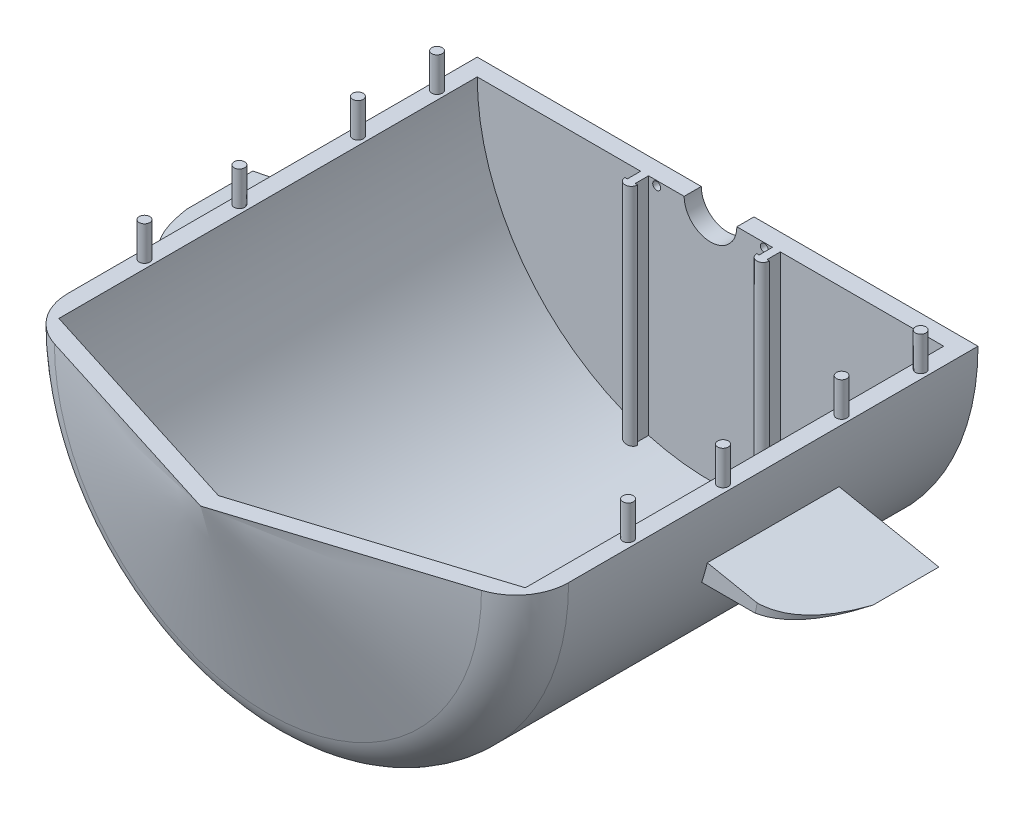
SolidWorks part; units mm, degrees
material "PVC 0.007 Plasticized"
ref_plane "Front Plane" through (0, 0, 0) normal (0, 0, 1) x (1, 0, 0)
ref_plane "Top Plane" through (0, 0, 0) normal (0, 1, 0) x (1, 0, 0)
ref_plane "Right Plane" through (0, 0, 0) normal (1, 0, 0) x (0, 0, -1)
sketch "Sketch1" plane through (0, 0, 0) normal (0, 1, 0) x (1, 0, 0)
  line L0 (0, 75) -> (95, 75)
  line L1 (95, 75) -> (95, -95)
  line L2 (95, -95) -> (0, -125)
  line L3 (0, -125) -> (0, 75) construction
  line L4 (0, 75) -> (0, -125)
  dimension "D1" = 200
  dimension "D2" = 170
  dimension "D3" = 95
  dimension "D4" = 75
  dimension "D5" = 95
revolve "Revolve1" add sketch "Sketch1" angle 180 about L3
sketch "Sketch2" plane through (0, 0, 0) normal (0, 1, 0) x (1, 0, 0)
  line L5 (0, 68.5) -> (0, -118.1836) construction
  line L6 (0, 68.5) -> (0, -118.1836)
  line L10 (-88.5, -90.2362) -> (0, -118.1836)
  line L11 (0, -118.1836) -> (88.5, -90.2362)
  line L12 (88.5, -90.2362) -> (88.5, 68.5)
  line L13 (88.5, 68.5) -> (-88.5, 68.5)
  line L14 (-88.5, 68.5) -> (-88.5, -90.2362)
  line L16 (0, -118.1836) -> (88.5, -90.2362)
  line L17 (88.5, -90.2362) -> (88.5, 68.5)
  line L18 (88.5, 68.5) -> (0, 68.5)
  dimension "D1" = 6.5
revolve "Cut-Revolve3" cut sketch "Sketch2" angle 360 about L5
sketch "Sketch3" plane through (0, 0, 0) normal (0, 1, 0) x (1, 0, 0)
  line L0 (-88.5, 68.5) -> (-95, 68.5) construction
  line L1 (-95, -95) -> (-95, 75) construction
  line L2 (-91.75, 68.5) -> (-91.75, -96.0263) construction
  line L3 (0, -125) -> (-95, -95) construction
  line L4 (0, 68.5) -> (0, -90.2362) construction
  line L5 (-88.5, 68.5) -> (88.5, 68.5) construction
  line L6 (88.5, -90.2362) -> (-88.5, -90.2362) construction
  circle A1 centre (-91.75, 56.5) radius 2
  circle A2 centre (-91.75, 26.5) radius 2
  circle A3 centre (-91.75, -18.5) radius 2
  circle A4 centre (-91.75, -54.5) radius 2
  circle A5 centre (91.75, -54.5) radius 2
  circle A6 centre (91.75, -18.5) radius 2
  circle A7 centre (91.75, 26.5) radius 2
  circle A8 centre (91.75, 56.5) radius 2
  dimension "D1" = 4
  dimension "D2" = 30
  dimension "D3" = 45
  dimension "D4" = 36
  dimension "D5" = 12
extrude "Boss-Extrude1" add sketch "Sketch3" along normal blind 13
sketch "Sketch4" plane through (0, 0, 0) normal (0, 0, 1) x (1, 0, 0)
  line L1 (88.5, 0) -> (-88.5, 0)
  line L2 (88.5, 0) -> (-88.5, 0)
  line L6 (0, -88.5) -> (0, -52) construction
  line L7 (-76.787, -44) -> (76.787, -44)
  line L8 (-71.6118, -52) -> (71.6118, -52)
  arc A1 (-88.5, 0) -> (88.5, 0) centre (0, 0) ccw
  arc A2 (-88.5, 0) -> (88.5, 0) centre (0, 0) ccw
  dimension "D1" = 0
  dimension "D2" = 44.5
  dimension "D3" = 8
sketch "Sketch5" plane through (0, 0, 0) normal (0, 1, 0) x (1, 0, 0)
  line L1 (23.5, 63.4476) -> (23.5, 68.5)
  line L4 (0, 0) -> (0, 89.957) construction
  line L8 (-27.4, 63.4476) -> (-26.5, 63.4476)
  line L9 (-26.5, 63.4476) -> (-26.5, 68.5)
  line L10 (-22.6, 63.4476) -> (-23.5, 63.4476)
  line L11 (-23.5, 63.4476) -> (-23.5, 68.5)
  line L12 (88.5, 68.5) -> (-88.5, 68.5) construction
  line L13 (-23.5, 68.5) -> (-26.5, 68.5)
  line L14 (22.6, 63.4476) -> (23.5, 63.4476)
  line L15 (27.4, 63.4476) -> (26.5, 63.4476)
  line L16 (26.5, 63.4476) -> (26.5, 68.5)
  line L17 (23.5, 68.5) -> (26.5, 68.5)
  arc A0 (-27.4, 63.4476) -> (-22.6, 63.4476) centre (-25, 63.4476) ccw
  arc A2 (27.4, 63.4476) -> (22.6, 63.4476) centre (25, 63.4476) cw
  dimension "D2" = 2.4
  dimension "D5" = 3
  dimension "D1" = 5.0524
  dimension "D3" = 25
extrude "Boss-Extrude8" add sketch "Sketch5" against normal up to surface (85.5657 mm away)
extrude "Boss-Extrude10" [suppressed] add sketch "Sketch4" along normal mid plane 120 contours L7 A2 L8
sketch "Sketch7" plane through (0, 0, -68.5) normal (0, 0, 1) x (1, 0, 0)
  line L0 (0, 0) -> (20.4252, -1.75) construction
  line L2 (0, 21.148) -> (0, -18.5427) construction
  line L3 (0, 0) -> (95, 0) construction
  circle A0 centre (0, 0) radius 10
  circle A1 centre (20.4252, -1.75) radius 1.5
  circle A2 centre (-20.4252, -1.75) radius 1.5
  dimension "D1" = 20
  dimension "D2" = 3
  dimension "D4" = 1.75
  dimension "D3" = 20.5
extrude "Cut-Extrude1" cut sketch "Sketch7" against normal blind 10
sketch "Sketch8" plane through (0, 0, 0) normal (0, 0, 1) x (1, 0, 0)
  line L0 (0, 0) -> (0, -30) construction
  line L1 (0, -30) -> (90.1388, -30) construction
  line L2 (90.1388, -30) -> (-90.1388, -30) construction
  line L3 (90.1388, -30) -> (130.1388, -30)
  line L4 (130.1388, -30) -> (92.2971, -22.5)
  line L5 (92.2971, -22.5) -> (90.1388, -30)
  line L6 (-130.1388, -30) -> (-92.2971, -22.5)
  line L7 (-90.1388, -30) -> (-130.1388, -30)
  line L8 (-92.2971, -22.5) -> (-90.1388, -30)
  arc A0 (-95, 0) -> (95, 0) centre (0, 0) ccw construction
  dimension "D1" = 40
  dimension "D2" = 7.5
  dimension "D3" = 30
extrude "Boss-Extrude11" add sketch "Sketch8" along normal mid plane 50
fillet "Fillet1" radius 20 1 edges at (0, -95, 95)
sketch "Sketch9" plane through (-0.8023, -4.0483, 0) normal (0.1944, 0.9809, 0) x (0.9809, -0.1944, 0)
  line L0 (133.4881, -25) -> (94.9103, -25) construction
  line L1 (133.4881, -25) -> (133.4881, 25) construction
  line L2 (145.027, -18.1656) -> (83.3714, -31.8344) construction
  line L3 (114.1992, -25) -> (133.4881, -25)
  line L4 (133.4881, -25) -> (133.4881, 0)
  spline S0 degree 2 poles (114.1992, -25) (127.4791, -22.0559) (133.4881, 0) knots 0 0 0 1 1 1
  point P8 (127.2881, -14.9526)
  dimension "D2" = 6.2
  dimension "D1" = 12.5
extrude "Cut-Extrude2" cut sketch "Sketch9" against normal blind 10
sketch "Sketch10" plane through (0.8023, -4.0483, 0) normal (-0.1944, 0.9809, 0) x (0.9809, 0.1944, 0)
  line L0 (-94.9103, -25) -> (-133.4881, -25) construction
  line L1 (-133.4881, -25) -> (-133.4881, 25) construction
  line L2 (-145.003, -18.0581) -> (-83.3955, -31.9419) construction
  line L3 (-114.1992, -25) -> (-133.4881, -25)
  line L4 (-133.4881, -25) -> (-133.4881, 0)
  spline S0 degree 2 poles (-114.1992, -25) (-129.6011, -21.529) (-133.4881, 0) knots 0 0 0 1 1 1
  point P8 (-127.2881, -16.2519)
  dimension "D1" = 12.7
  dimension "D2" = 6.2
extrude "Cut-Extrude3" cut sketch "Sketch10" against normal blind 10
